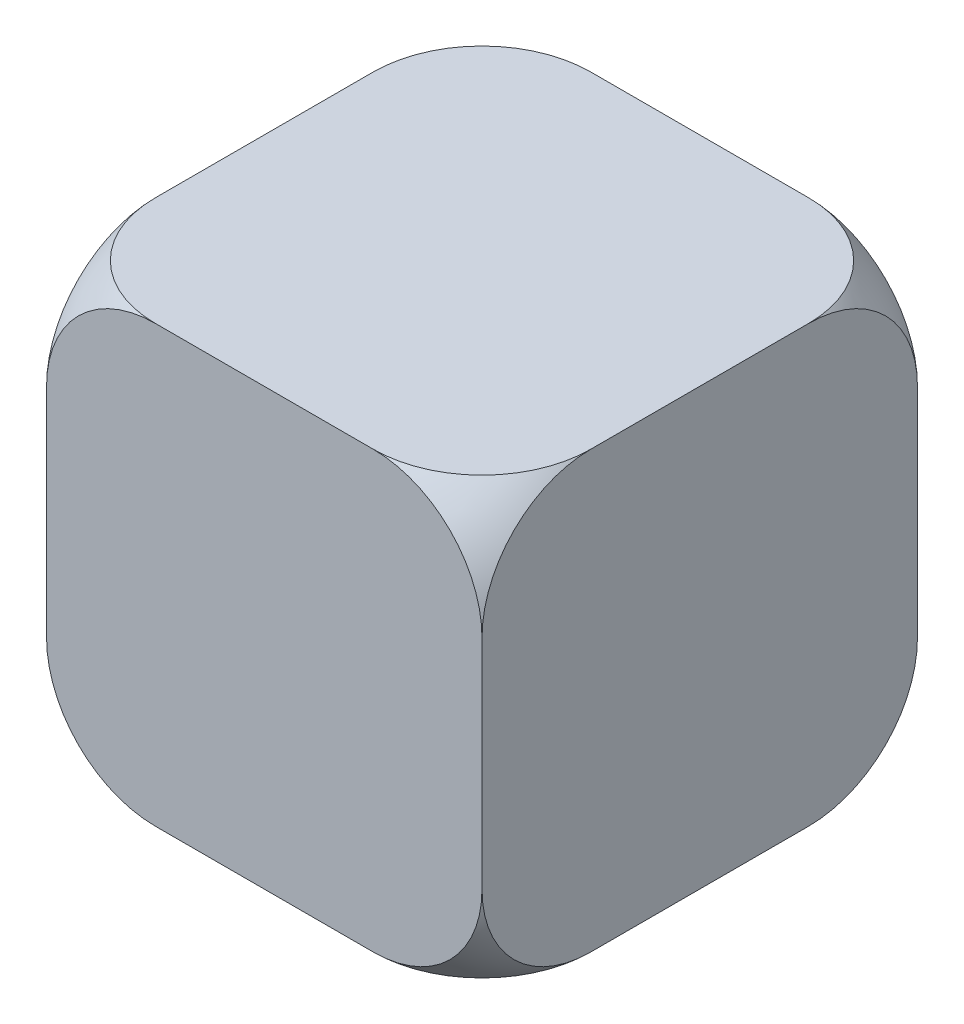
SolidWorks part; units mm, degrees
ref_plane "Plano frontal" through (0, 0, 0) normal (0, 0, 1) x (1, 0, 0)
ref_plane "Plano superior" through (0, 0, 0) normal (0, 1, 0) x (1, 0, 0)
ref_plane "Plano direito" through (0, 0, 0) normal (1, 0, 0) x (0, 0, -1)
sketch3d "3DSketch1"
  line L0 (0, 0, 0) -> (2.5, 0, 0) construction
  line L1 (2.5, 0, 0) -> (7.5, 0, 0) construction
  line L2 (7.5, 0, 0) -> (10, 0, 0) construction
  line L3 (0, 0, 0) -> (0, 0, 2.5) construction
  line L4 (0, 0, 2.5) -> (0, 0, 7.5) construction
  line L5 (0, 0, 7.5) -> (0, 0, 10) construction
  line L6 (10, 0, 0) -> (10, 0, 2.5) construction
  line L7 (0, 0, 10) -> (2.5, 0, 10) construction
  line L8 (10, 0, 2.5) -> (10, 0, 7.5) construction
  line L9 (2.5, 0, 10) -> (7.5, 0, 10) construction
  line L10 (10, 0, 7.5) -> (10, 0, 10) construction
  line L11 (7.5, 0, 10) -> (10, 0, 10) construction
  line L12 (0, 0, 7.5) -> (2.5, 0, 7.5) construction
  line L13 (2.5, 0, 10) -> (2.5, 0, 7.5) construction
  line L14 (10, 0, 7.5) -> (7.5, 0, 7.5) construction
  line L15 (7.5, 0, 10) -> (7.5, 0, 7.5) construction
  line L16 (2.5, 0, 7.5) -> (2.5, 2.5, 7.5) construction
  line L17 (7.5, 0, 7.5) -> (7.5, 2.5, 7.5) construction
  line L18 (2.5, 2.5, 7.5) -> (2.5, 7.5, 7.5) construction
  line L19 (7.5, 2.5, 7.5) -> (7.5, 7.5, 7.5) construction
  line L20 (2.5, 7.5, 7.5) -> (2.5, 10, 7.5) construction
  line L21 (7.5, 7.5, 7.5) -> (7.5, 10, 7.5) construction
  line L22 (0, 0, 2.5) -> (2.5, 0, 2.5) construction
  line L23 (2.5, 0, 2.5) -> (2.5, 2.5, 2.5) construction
  line L24 (2.5, 0, 0) -> (2.5, 0, 2.5) construction
  line L25 (2.5, 2.5, 2.5) -> (2.5, 7.5, 2.5) construction
  line L26 (10, 0, 2.5) -> (7.5, 0, 2.5) construction
  line L27 (2.5, 7.5, 2.5) -> (2.5, 10, 2.5) construction
  line L28 (7.5, 0, 0) -> (7.5, 0, 2.5) construction
  line L29 (7.5, 0, 2.5) -> (7.5, 2.5, 2.5) construction
  line L30 (7.5, 2.5, 2.5) -> (7.5, 7.5, 2.5) construction
  line L31 (7.5, 7.5, 2.5) -> (7.5, 10, 2.5) construction
  line L32 (2.5, 0, 2.5) -> (5, 0, 2.5) construction
  line L33 (7.5, 0, 2.5) -> (5, 0, 2.5) construction
  line L34 (2.5, 2.5, 2.5) -> (-1.0355, 2.5, 2.5)
  line L35 (2.5, 2.5, 2.5) -> (6.0355, 2.5, 2.5)
  line L36 (7.5, 2.5, 2.5) -> (3.9645, 2.5, 2.5)
  line L37 (7.5, 2.5, 2.5) -> (11.0355, 2.5, 2.5)
  arc A0 (-1.0355, 2.5, 2.5) -> (6.0355, 2.5, 2.5) centre (2.5, 2.5, 2.5) ccw
  arc A1 (3.9645, 2.5, 2.5) -> (11.0355, 2.5, 2.5) centre (7.5, 2.5, 2.5) ccw
  point P32 (2.5, 2.5, 6.0355)
  point P34 (7.5, 2.5, 6.0355)
  dimension "D1" = 2.5
  dimension "D2" = 2.5
  dimension "D3" = 10
  dimension "D4" = 2.5
  dimension "D5" = 2.5
  dimension "D6" = 10
  dimension "D7" = 2.5
  dimension "D8" = 2.5
  dimension "D9" = 2.5
  dimension "D10" = 2.5
  dimension "D11" = 2.5
  dimension "D12" = 2.5
  dimension "D13" = 2.5
  dimension "D14" = 2.5
  dimension "D15" = 10
  dimension "D16" = 10
  dimension "D17" = 2.5
  dimension "D18" = 2.5
  dimension "D19" = 10
  dimension "D20" = 2.5
  dimension "D21" = 2.5
  dimension "D22" = 10
  dimension "D23" = 2.5
  dimension "D24" = 2.5
ref_plane "Plano1" through (0, 0, 2.5) normal (0, 0, 1) x (1, 0, 0)
sketch "Esboço2" plane through (0, 0, 2.5) normal (0, 0, 1) x (1, 0, 0)
  line L0 (2.5, 2.5) -> (-1.0355, 2.5) construction
  line L1 (2.5, 2.5) -> (6.0355, 2.5) construction
  line L2 (2.5, 2.5) -> (-1.0355, 2.5)
  line L3 (2.5, 2.5) -> (6.0355, 2.5)
  line L4 (7.5, 2.5) -> (3.9645, 2.5) construction
  line L5 (7.5, 2.5) -> (11.0355, 2.5) construction
  line L6 (7.5, 2.5) -> (3.9645, 2.5)
  line L7 (7.5, 2.5) -> (11.0355, 2.5)
  arc A0 (-1.0355, 2.5) -> (6.0355, 2.5) centre (2.5, 2.5) ccw construction
  arc A1 (-1.0355, 2.5) -> (6.0355, 2.5) centre (2.5, 2.5) ccw
  arc A2 (3.9645, 2.5) -> (11.0355, 2.5) centre (7.5, 2.5) ccw construction
  arc A3 (3.9645, 2.5) -> (11.0355, 2.5) centre (7.5, 2.5) ccw
revolve "Revolução1" add sketch "Esboço2" angle 360 about L2
pattern_linear "Padrão linear2" count 2 spacing 5 along (0, 0, 1) count 2 spacing 5 along (0, 1, 0) of bodies 152 102 101
sketch "Esboço3" plane through (0, 0, 0) normal (0, 0, 1) x (1, 0, 0)
  line L0 (2.5, 7.5) -> (2.5, 10)
  line L1 (0, 0) -> (2.5, 0)
  line L2 (0, 0) -> (0, 2.5)
  line L3 (0, 10) -> (2.5, 10)
  line L4 (10, 0) -> (10, 2.5)
  line L5 (-5, -5) -> (15, -5)
  line L6 (-5, -5) -> (-5, 15)
  line L7 (-5, 15) -> (15, 15)
  line L8 (15, -5) -> (15, 15)
  line L9 (2.5, 7.5) -> (0, 7.5)
  line L10 (2.5, 2.5) -> (2.5, 0)
  line L11 (2.5, 2.5) -> (0, 2.5)
  line L12 (7.5, 2.5) -> (7.5, 0)
  line L13 (7.5, 2.5) -> (10, 2.5)
  line L14 (7.5, 7.5) -> (10, 7.5)
  line L15 (7.5, 7.5) -> (7.5, 10)
  line L16 (10, 7.5) -> (10, 10)
  line L17 (0, 7.5) -> (0, 10)
  line L18 (7.5, 0) -> (10, 0)
  line L19 (7.5, 10) -> (10, 10)
  circle A0 centre (7.5, 7.5) radius 3.5355 construction
  circle A1 centre (2.5, 7.5) radius 3.5355 construction
  circle A2 centre (2.5, 2.5) radius 3.5355 construction
  circle A3 centre (7.5, 2.5) radius 3.5355 construction
  circle A4 centre (7.5, 7.5) radius 3.5355 construction
  circle A5 centre (2.5, 7.5) radius 3.5355 construction
  circle A6 centre (2.5, 2.5) radius 3.5355 construction
  circle A7 centre (7.5, 2.5) radius 3.5355 construction
  dimension "D1" = 10
  dimension "D2" = 5
  dimension "D3" = 5
  dimension "D4" = 5
  dimension "D5" = 5
  dimension "D6" = 10
extrude "Corte-extrusão1" cut sketch "Esboço3" against normal through all and the other way through all
sketch "Esboço4" plane through (0, 0, 0) normal (1, 0, 0) x (0, 0, -1)
  line L0 (-7.5, 7.5) -> (-10, 7.5)
  line L1 (0, 0) -> (-2.5, 0)
  line L2 (0, 0) -> (0, 2.5)
  line L3 (0, 10) -> (-2.5, 10)
  line L4 (-10, 0) -> (-10, 2.5)
  line L5 (-15, 15) -> (5, 15)
  line L6 (-15, 15) -> (-15, -5)
  line L7 (-15, -5) -> (5, -5)
  line L8 (5, 15) -> (5, -5)
  line L9 (-5, 7.5) -> (-10, 7.5) construction
  line L10 (-7.5, 7.5) -> (-7.5, 10)
  line L11 (-7.5, 2.5) -> (-7.5, 0)
  line L12 (-5, 2.5) -> (-10, 2.5) construction
  line L13 (-7.5, 2.5) -> (-10, 2.5)
  line L14 (-2.5, 2.5) -> (-2.5, 0)
  line L15 (0, 2.5) -> (-5, 2.5) construction
  line L16 (-2.5, 2.5) -> (0, 2.5)
  line L17 (-2.5, 7.5) -> (0, 7.5)
  line L18 (0, 7.5) -> (-5, 7.5) construction
  line L19 (-2.5, 7.5) -> (-2.5, 10)
  line L20 (-10, 7.5) -> (-10, 10)
  line L21 (0, 7.5) -> (0, 10)
  line L22 (-7.5, 0) -> (-10, 0)
  line L23 (-7.5, 10) -> (-10, 10)
  dimension "D2" = 5
  dimension "D3" = 5
  dimension "D4" = 5
  dimension "D5" = 5
extrude "Corte-extrusão3" cut sketch "Esboço4" against normal blind 10 and the other way blind 20
sketch "Esboço5" plane through (0, 0, 2.5) normal (0, 0, 1) x (1, 0, 0)
  line L1 (10, 10) -> (0, 10)
  line L2 (10, 10) -> (10, 0)
  line L3 (10, 0) -> (0, 0)
  line L4 (0, 10) -> (0, 0)
extrude "Ressalto-extrusão1" add sketch "Esboço5" along normal up to vertex (5 mm away) up to point (7.5, 7.5, 7.5)
sketch "Esboço6" plane through (2.5, 0, 0) normal (1, 0, 0) x (0, 0, -1)
  line L1 (-10, 10) -> (0, 10)
  line L2 (-10, 10) -> (-10, 0)
  line L3 (-10, 0) -> (0, 0)
  line L4 (0, 10) -> (0, 0)
extrude "Ressalto-extrusão2" add sketch "Esboço6" along normal up to vertex (5 mm away) up to point (7.5, 7.5, 7.5)
sketch "Esboço7" plane through (0, 2.5, 0) normal (0, 1, 0) x (1, 0, 0)
  line L1 (10, -10) -> (0, -10)
  line L2 (10, -10) -> (10, 0)
  line L3 (10, 0) -> (0, 0)
  line L4 (0, -10) -> (0, 0)
extrude "Ressalto-extrusão3" add sketch "Esboço7" along normal up to vertex (5 mm away) up to point (7.5, 7.5, 7.5)
